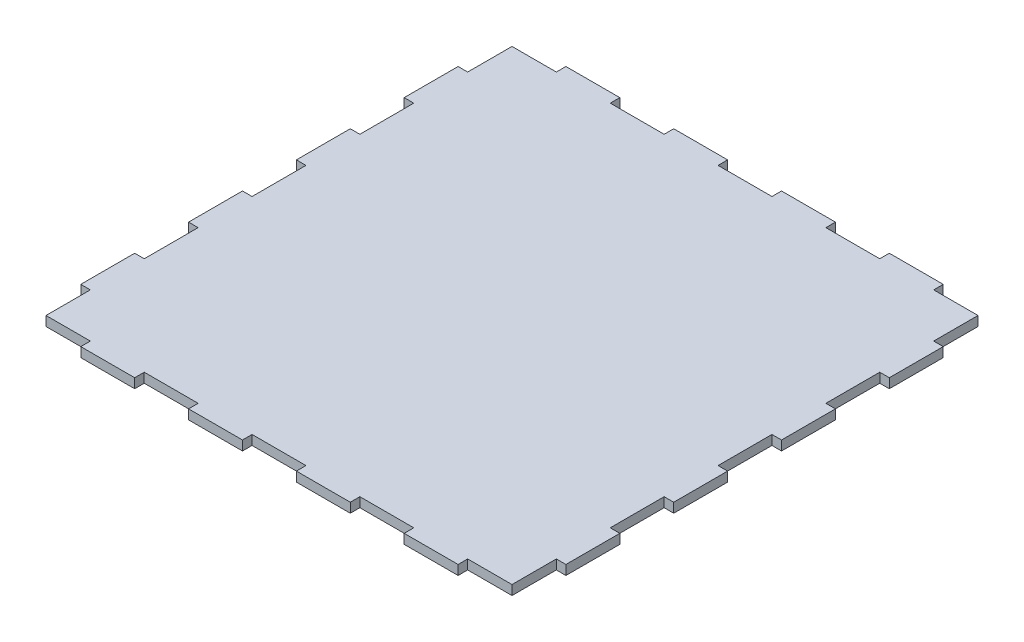
SolidWorks part; units mm, degrees
ref_plane "Front Plane" through (0, 0, 0) normal (0, 0, 1) x (1, 0, 0)
ref_plane "Top Plane" through (0, 0, 0) normal (0, 1, 0) x (1, 0, 0)
ref_plane "Right Plane" through (0, 0, 0) normal (1, 0, 0) x (0, 0, -1)
sketch "Sketch1" plane through (0, 0, 0) normal (0, 1, 0) x (1, 0, 0)
  line L0 (-73, -59.1111) -> (-73, -73)
  line L1 (-76, -76) -> (76, -76) construction
  line L2 (-76, -76) -> (-76, 76) construction
  line L3 (-76, 76) -> (76, 76) construction
  line L4 (76, -76) -> (76, 76) construction
  line L5 (0, 76) -> (0, -76) construction
  line L6 (-76, 0) -> (76, 0) construction
  line L7 (-73, -73) -> (-59.1111, -73)
  line L8 (-59.1111, -73) -> (-59.1111, -76)
  line L9 (-59.1111, -76) -> (-42.2222, -76)
  line L10 (-42.2222, -76) -> (-42.2222, -73)
  line L11 (-42.2222, -73) -> (-25.3333, -73)
  line L12 (-25.3333, -73) -> (-25.3333, -76)
  line L13 (-25.3333, -76) -> (-8.4444, -76)
  line L14 (-8.4444, -76) -> (-8.4444, -73)
  line L15 (-8.4444, -73) -> (0, -73)
  line L16 (-73, -59.1111) -> (-76, -59.1111)
  line L17 (-76, -59.1111) -> (-76, -42.2222)
  line L18 (-76, -42.2222) -> (-73, -42.2222)
  line L19 (-73, -42.2222) -> (-73, -25.3333)
  line L20 (-73, -25.3333) -> (-76, -25.3333)
  line L21 (-76, -25.3333) -> (-76, -8.4444)
  line L22 (-76, -8.4444) -> (-73, -8.4444)
  line L23 (-73, 0) -> (-73, -8.4444)
  line L24 (-73, 0) -> (0, 0)
  line L25 (0, 0) -> (0, -73)
  point P80 (0, 0)
  dimension "D1" = 152
  dimension "D2" = 3
  dimension "D3" = 3
  dimension "D4" = 16.8889
  dimension "D5" = 13.8889
extrude "Boss-Extrude1" add sketch "Sketch1" along normal blind 3
mirror "Mirror1" about plane through (0, 0, 0) normal (1, 0, 0) of "Boss-Extrude1"
